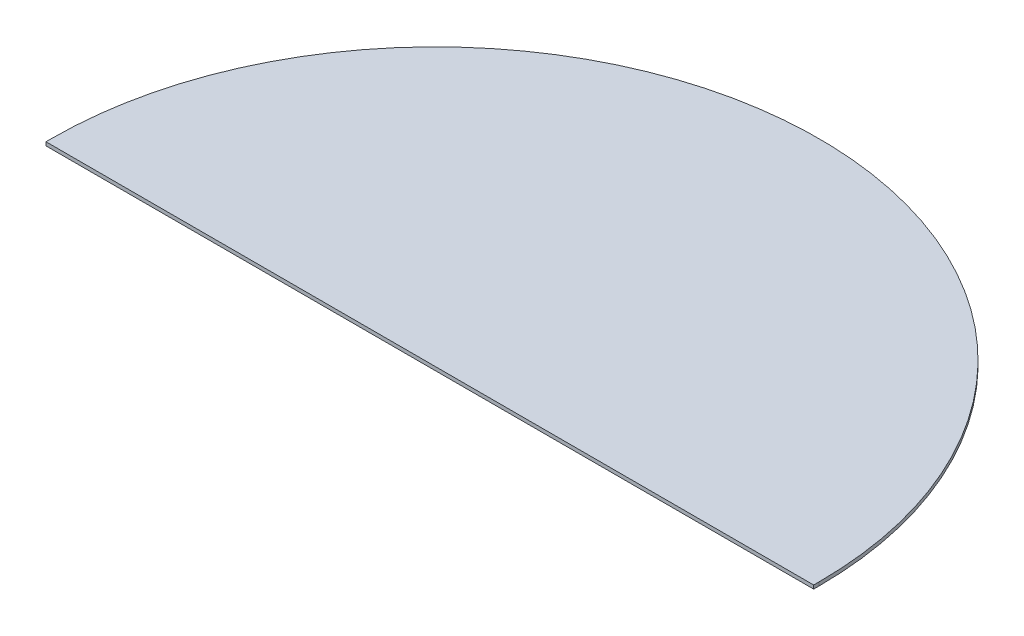
SolidWorks part; units mm, degrees
ref_plane "Front Plane" through (0, 0, 0) normal (0, 0, 1) x (1, 0, 0)
ref_plane "Top Plane" through (0, 0, 0) normal (0, 1, 0) x (1, 0, 0)
ref_plane "Right Plane" through (0, 0, 0) normal (1, 0, 0) x (0, 0, -1)
sketch "Sketch1" plane through (0, 0, 0) normal (0, 1, 0) x (1, 0, 0)
  line L0 (0, 0) -> (0, -15)
  line L1 (0, -15) -> (2130, -15)
  line L2 (2130, -15) -> (2130, 0)
  arc A0 (0, 0) -> (2130, 0) centre (1065, 0) cw
  dimension "D1" = 1065
  dimension "D2" = 15
extrude "Boss-Extrude1" add sketch "Sketch1" along normal blind 10
